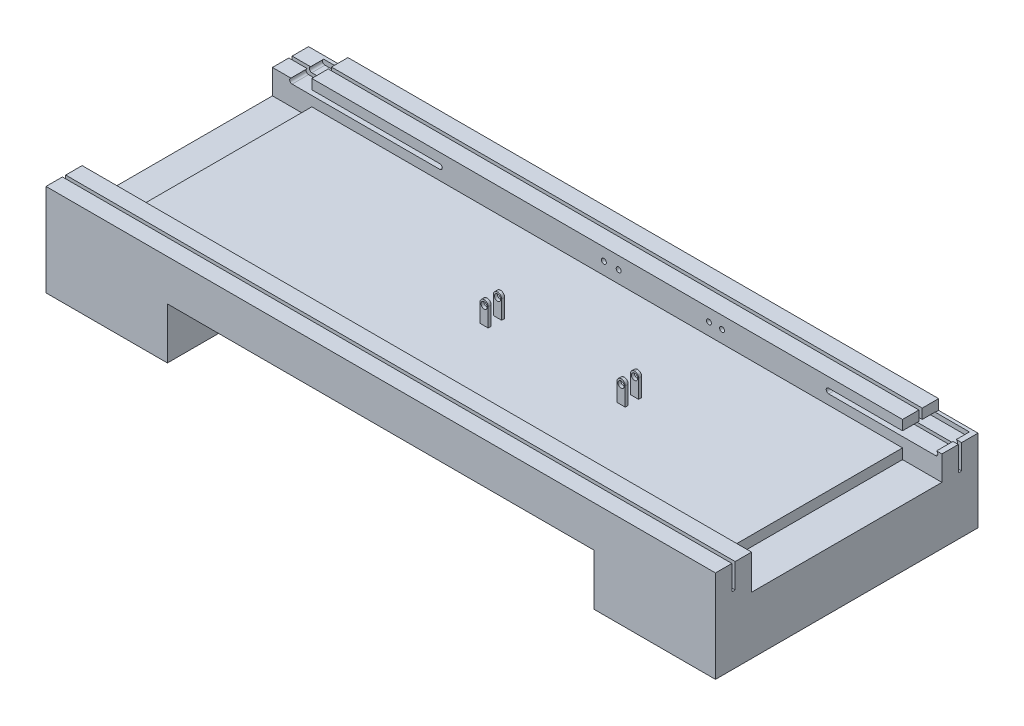
SolidWorks part; units mm, degrees
ref_plane "Front Plane" through (0, 0, 0) normal (0, 0, 1) x (1, 0, 0)
ref_plane "Top Plane" through (0, 0, 0) normal (0, 1, 0) x (1, 0, 0)
ref_plane "Right Plane" through (0, 0, 0) normal (1, 0, 0) x (0, 0, -1)
sketch "Sketch1" plane through (0, 0, 0) normal (0, 0, 1) x (1, 0, 0)
  line L0 (-1435.0087, 0) -> (1435.0087, 0) construction
  line L1 (0, 937.435) -> (0, -937.435) construction
  line L2 (-900, 213.5157) -> (900, 213.5157)
  line L3 (900, 213.5157) -> (900, -67.5043)
  line L4 (900, -67.5043) -> (500, -67.5043)
  line L5 (500, -67.5043) -> (500, -267.5043) construction
  line L6 (500, -267.5043) -> (-500, -267.5043) construction
  line L7 (-500, -67.5043) -> (-500, -267.5043) construction
  line L8 (-900, -67.5043) -> (-500, -67.5043)
  line L9 (-900, 213.5157) -> (-900, -67.5043)
  line L10 (-500, -67.5043) -> (500, -67.5043)
  point P4 (0, 0)
  point P8 (0, 0)
  point P11 (0, 213.5157)
  point P16 (0, -267.5043)
  dimension "D1" = 1800
  dimension "D2" = 400
  dimension "D3" = 281.02
  dimension "D4" = 200
  dimension "D5" = 267.5043
extrude "General shape" add sketch "Sketch1" along normal blind 800
ref_plane "Plane2" through (0, 0, 400) normal (0, 0, -1) x (-1, 0, 0)
sketch "Sketch5" plane through (0, 213.5157, 0) normal (0, 1, 0) x (1, 0, 0)
  line L0 (900, -50) -> (900, -750)
  line L1 (900, -750) -> (-900, -750)
  line L2 (-900, -750) -> (-900, -50)
  line L3 (-900, -50) -> (900, -50)
  line L4 (900, 0) -> (-900, 0) construction
  line L5 (900, -800) -> (-900, -800) construction
  line L6 (900, -800) -> (900, 0) construction
  line L7 (-900, -800) -> (-900, 0) construction
  dimension "D1" = 50
  dimension "D2" = 50
  dimension "D3" = 0
  dimension "D4" = 0
extrude "Cut-Extrude2" cut sketch "Sketch5" against normal blind 75
sketch "Sketch6" plane through (0, 0, 0) normal (0, 0, -1) x (-1, 0, 0)
  line L0 (-900, -67.5043) -> (-900, 213.5157) construction
  line L6 (-650, 88.5157) -> (650, 88.5157)
  line L7 (-650, 88.5157) -> (-650, -67.5043)
  line L10 (-650, -67.5043) -> (650, -67.5043)
  line L11 (650, 88.5157) -> (650, -67.5043)
  point P4 (0, 88.5157)
  dimension "D1" = 50
  dimension "D2" = 250
extrude "Weight reduction" cut sketch "Sketch6" against normal through all
sketch "Sketch8" plane through (0, 0, 0) normal (1, 0, 0) x (0, 0, -1)
  line L0 (-740, 138.5157) -> (-740, 213.5157)
  line L1 (-750, 138.5157) -> (-50, 138.5157) construction
  line L2 (-740, 213.5157) -> (-690, 213.5157)
  line L3 (-690, 213.5157) -> (-690, 138.5157)
  line L4 (-690, 138.5157) -> (-740, 138.5157)
  line L5 (-750, 138.5157) -> (-750, 213.5157) construction
  line L6 (-400, -154.561) -> (-400, 154.561) construction
  line L7 (-60, 138.5157) -> (-60, 213.5157)
  line L8 (-110, 138.5157) -> (-60, 138.5157)
  line L9 (-110, 213.5157) -> (-110, 138.5157)
  line L10 (-60, 213.5157) -> (-110, 213.5157)
  dimension "D1" = 50
  dimension "D2" = 10
  dimension "D3" = 75
extrude "Boss-Extrude3" add sketch "Sketch8" along normal blind 900 and the other way blind 900
sketch "Sketch9" plane through (900, 0, 0) normal (1, 0, 0) x (0, 0, -1)
  line L0 (-800, 213.5157) -> (-750, 213.5157)
  line L1 (-800, 213.5157) -> (-750, 213.5157) construction
  line L2 (-750, 213.5157) -> (-750, 138.5157)
  line L3 (-750, 138.5157) -> (-740, 138.5157)
  line L4 (-740, 138.5157) -> (-740, 213.5157)
  line L5 (-740, 213.5157) -> (-690, 213.5157)
  line L6 (-690, 213.5157) -> (-690, 107.4957)
  line L7 (-690, 138.5157) -> (-690, 213.5157) construction
  line L8 (-690, 107.4957) -> (-110, 107.4957)
  line L12 (0, -67.5043) -> (-800, -67.5043)
  line L13 (-800, -67.5043) -> (-800, 213.5157)
  line L14 (-110, 182.4957) -> (-110, 107.4957)
  line L15 (0, 182.4957) -> (-50, 182.4957)
  line L16 (-50, 182.4957) -> (-50, 107.4957)
  line L17 (0, -67.5043) -> (0, 182.4957)
  line L18 (-60, 182.4957) -> (-110, 182.4957)
  line L19 (-50, 107.4957) -> (-60, 107.4957)
  line L20 (-60, 107.4957) -> (-60, 182.4957)
  dimension "D1" = 580
  dimension "D2" = 10
  dimension "D3" = 50
  dimension "D4" = 50
  dimension "D5" = 75
extrude "Boss-Extrude4" add sketch "Sketch9" along normal blind 120
sketch "Sketch10" plane through (-900, 0, 0) normal (-1, 0, 0) x (0, 0, 1)
  line L0 (800, 213.5157) -> (750, 213.5157)
  line L1 (750, 213.5157) -> (800, 213.5157) construction
  line L2 (750, 213.5157) -> (750, 138.5157)
  line L3 (740, 138.5157) -> (740, 213.5157)
  line L4 (740, 213.5157) -> (690, 213.5157)
  line L5 (690, 213.5157) -> (690, 107.4957)
  line L6 (690, 107.4957) -> (110, 107.4957)
  line L7 (110, 107.4957) -> (110, 182.4957)
  line L8 (110, 182.4957) -> (60, 182.4957)
  line L9 (60, 182.4957) -> (60, 107.4957)
  line L10 (60, 107.4957) -> (50, 107.4957)
  line L11 (50, 107.4957) -> (50, 182.4957)
  line L12 (0, 182.4957) -> (50, 182.4957) construction
  line L13 (50, 182.4957) -> (50, 107.4957) construction
  line L14 (50, 182.4957) -> (0, 182.4957)
  line L15 (0, 182.4957) -> (0, -67.5043)
  line L16 (0, -67.5043) -> (800, -67.5043)
  line L17 (800, -67.5043) -> (800, 213.5157)
  line L18 (750, 138.5157) -> (740, 138.5157)
  line L19 (110, 107.4957) -> (690, 107.4957) construction
  line L20 (110, 213.5157) -> (110, 138.5157) construction
  line L21 (60, 138.5157) -> (60, 213.5157) construction
  line L22 (0, 213.5157) -> (0, -67.5043) construction
  line L23 (50, 107.4957) -> (60, 107.4957) construction
  point P36 (0, 0)
  point P37 (0, 0)
  point P38 (0, 0)
  point P39 (0, 0)
  point P40 (0, 0)
  point P41 (0, 0)
  point P42 (0, 0)
  point P43 (0, 0)
  point P44 (0, 0)
extrude "Boss-Extrude5" add sketch "Sketch10" along normal blind 120
sketch "Sketch7" plane through (0, 0, 750) normal (0, 0, -1) x (-1, 0, 0)
  line L0 (0, 800.1675) -> (0, -800.1675) construction
  line L1 (-1193.3565, 176.0157) -> (1193.3565, 176.0157) construction
  line L2 (-900, 213.5157) -> (900, 213.5157) construction
  line L3 (1020, 73.0057) -> (1020, 372.8849) construction
  line L4 (1020, -67.5043) -> (1020, 213.5157) construction
  line L7 (960, 176.0157) -> (510, 176.0157) construction
  line L10 (960, 168.5157) -> (510, 168.5157)
  line L13 (-1020, 107.4957) -> (-1020, 213.5157) construction
  line L16 (-1000, 176.0157) -> (-675, 176.0157) construction
  line L17 (-1000, 183.5157) -> (-675, 183.5157)
  line L18 (-1000, 168.5157) -> (-675, 168.5157)
  line L19 (960, 183.5157) -> (510, 183.5157)
  circle A7 centre (-35, 176.0157) radius 7.5
  circle A9 centre (-350, 176.0157) radius 7.5
  arc A19 (-1000, 183.5157) -> (-1000, 168.5157) centre (-1000, 176.0157) ccw
  arc A20 (-675, 168.5157) -> (-675, 183.5157) centre (-675, 176.0157) ccw
  circle A21 centre (-310, 176.0157) radius 7.5
  arc A22 (960, 168.5157) -> (960, 183.5157) centre (960, 176.0157) ccw
  arc A23 (510, 183.5157) -> (510, 168.5157) centre (510, 176.0157) ccw
  circle A24 centre (10, 176.0157) radius 7.5
  point P4 (0, 0)
  point P8 (0, 144.9957)
  point P15 (735, 176.0157)
  point P29 (-837.5, 176.0157)
  dimension "D3" = 10
  dimension "D4" = 7.5
  dimension "D5" = 450
  dimension "D6" = 500
  dimension "D7" = 15
  dimension "D13" = 40
  dimension "D14" = 15
  dimension "D16" = 15
  dimension "D17" = 15
  dimension "D18" = 275
  dimension "D19" = 20
  dimension "D20" = 325
  dimension "D22" = 7.5
  dimension "D26" = 325
  dimension "D1" = 37.5
extrude "Cut-Extrude4" cut sketch "Sketch7" against normal blind 40 and the other way blind 740
sketch "Sketch12" plane through (0, 0, 400) normal (0, 0, -1) x (-1, 0, 0)
  line L0 (1020, 213.5157) -> (1020, 138.5157) construction
  line L1 (1020, -67.5043) -> (1020, 213.5157) construction
  line L2 (1020, 138.5157) -> (-1910.404, 138.5157) construction
  line L8 (72.5, 138.5157) -> (72.5, 194.6157)
  line L9 (60.1, 207.0157) -> (59.9, 207.0157)
  line L10 (47.5, 194.6157) -> (47.5, 138.5157)
  line L11 (47.5, 138.5157) -> (72.5, 138.5157)
  line L12 (-345, 138.5157) -> (-345, 194.6157)
  line L13 (-357.4, 207.0157) -> (-357.6, 207.0157)
  line L14 (-370, 194.6157) -> (-370, 138.5157)
  line L15 (-370, 138.5157) -> (-345, 138.5157)
  line L16 (-1020, 213.5157) -> (-1020, -67.5043) construction
  circle A3 centre (60, 192.0157) radius 9.525
  arc A4 (72.5, 194.6157) -> (60.1, 207.0157) centre (60.1, 194.6157) ccw
  arc A5 (59.9, 207.0157) -> (47.5, 194.6157) centre (59.9, 194.6157) ccw
  circle A6 centre (-357.5, 192.0157) radius 9.525
  arc A7 (-357.6, 207.0157) -> (-370, 194.6157) centre (-357.6, 194.6157) ccw
  arc A8 (-345, 194.6157) -> (-357.4, 207.0157) centre (-357.4, 194.6157) ccw
  point P14 (72.5, 207.0157)
  point P17 (47.5, 207.0157)
  point P27 (-370, 207.0157)
  point P30 (-345, 207.0157)
  dimension "D5" = 68.5
  dimension "D6" = 15
  dimension "D4" = 12.5
  dimension "D2" = 19.05
  dimension "D3" = 25
  dimension "D7" = 12.4
  dimension "D8" = 960
  dimension "D11" = 12.5
  dimension "D12" = 19.05
  dimension "D13" = 12.4
  dimension "D14" = 15
  dimension "D1" = 75
  dimension "D9" = 25
  dimension "D10" = 68.5
  dimension "D15" = 650
extrude "Boss-Extrude6" add sketch "Sketch12" along normal blind 25 and the other way blind 25
sketch "Sketch13" plane through (-72.5, 0, 0) normal (-1, 0, 0) x (0, 0, 1)
  line L0 (415.875, 138.5157) -> (415.875, 207.0157)
  line L1 (425, 138.5157) -> (375, 138.5157) construction
  line L4 (384.125, 207.0157) -> (384.125, 138.5157)
  line L5 (384.125, 138.5157) -> (415.875, 138.5157)
  line L6 (425, 194.6157) -> (425, 138.5157) construction
  line L7 (425, 207.0157) -> (375, 207.0157) construction
  line L8 (415.875, 207.0157) -> (384.125, 207.0157)
  dimension "D1" = 31.75
  dimension "D2" = 9.125
extrude "Cut-Extrude5" cut sketch "Sketch13" against normal through all
